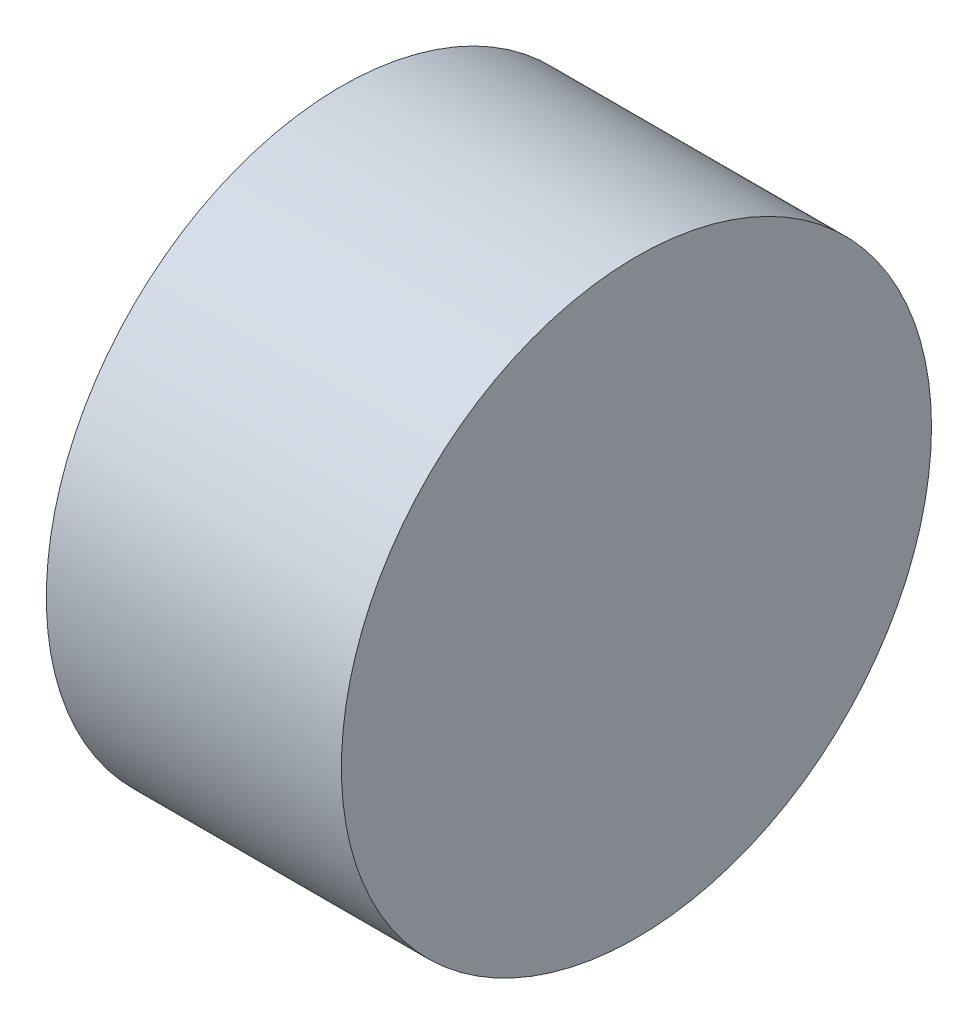
SolidWorks part; units mm, degrees
material "Titanium"
ref_plane "Front Plane" through (0, 0, 0) normal (0, 0, 1) x (1, 0, 0)
ref_plane "Top Plane" through (0, 0, 0) normal (0, 1, 0) x (1, 0, 0)
ref_plane "Right Plane" through (0, 0, 0) normal (1, 0, 0) x (0, 0, -1)
sketch "Sketch2" plane through (0, 0, 0) normal (1, 0, 0) x (0, 0, -1)
  circle A0 centre (0, 0) radius 5
  dimension "D1" = 10
extrude "Boss-Extrude1" add sketch "Sketch2" along normal blind 5
